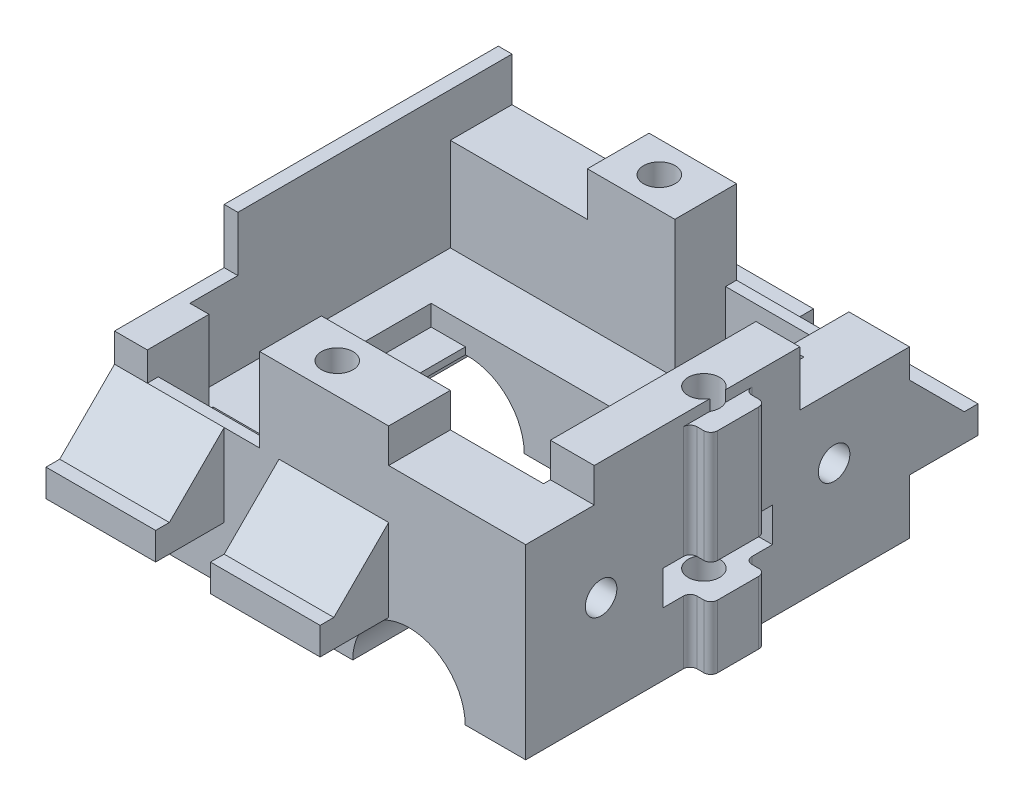
SolidWorks part; units mm, degrees
ref_plane "Front Plane" through (0, 0, 0) normal (0, 0, 1) x (1, 0, 0)
ref_plane "Top Plane" through (0, 0, 0) normal (0, 1, 0) x (1, 0, 0)
ref_plane "Right Plane" through (0, 0, 0) normal (1, 0, 0) x (0, 0, -1)
sketch "Sketch1" plane through (0, 0, 0) normal (1, 0, 0) x (0, 0, -1)
  line L0 (-26.7015, -9.0408) -> (-32.3015, -9.0408) construction
  line L1 (-60.7015, 7.0592) -> (-32.7015, 7.0592)
  line L2 (-60.7015, 7.0592) -> (-60.7015, -9.0408)
  line L3 (-60.7015, -9.0408) -> (-32.7015, -9.0408)
  line L4 (-32.7015, 7.0592) -> (-32.7015, -9.0408)
  dimension "D1" = 16.1
  dimension "D2" = 28
extrude "Boss-Extrude1" add sketch "Sketch1" along normal blind 30
sketch "Sketch2" plane through (0, 0, 60.7015) normal (0, 0, 1) x (1, 0, 0)
  line L7 (30, 7.0592) -> (20, 7.0592)
  line L8 (30, 7.0592) -> (30, 4.5592)
  line L9 (30, 4.5592) -> (20, 4.5592)
  line L10 (20, 7.0592) -> (20, 4.5592)
  dimension "D1" = 10
  dimension "D2" = 2.5
extrude "Cut-Extrude1" cut sketch "Sketch2" against normal blind 5
sketch "Sketch3" plane through (0, 0, 60.7015) normal (0, 0, 1) x (1, 0, 0)
  line L0 (0, 7.0592) -> (0, -9.0408) construction
  line L1 (0, 3.0592) -> (10, 3.0592)
  line L2 (0, 3.0592) -> (0, 7.0592)
  line L3 (0, 7.0592) -> (10, 7.0592)
  line L4 (10, 3.0592) -> (10, 7.0592)
  line L5 (20, 7.0592) -> (0, 7.0592) construction
  dimension "D1" = 4
  dimension "D2" = 10
extrude "Cut-Extrude2" cut sketch "Sketch3" against normal blind 8
sketch "Sketch4" plane through (0, 0, 32.7015) normal (0, 0, -1) x (-1, 0, 0)
  line L6 (-30, 7.0592) -> (0, 7.0592) construction
  line L7 (-1, 7.0592) -> (-11, 7.0592)
  line L8 (-1, 7.0592) -> (-1, 3.8592)
  line L9 (-1, 3.8592) -> (-11, 3.8592)
  line L10 (-11, 7.0592) -> (-11, 3.8592)
  line L11 (0, -9.0408) -> (0, 7.0592) construction
  dimension "D1" = 10
  dimension "D2" = 1
  dimension "D3" = 3.2
extrude "Cut-Extrude3" cut sketch "Sketch4" against normal blind 8
sketch "Sketch5" plane through (0, 0, 32.7015) normal (0, 0, -1) x (-1, 0, 0)
  line L0 (-30, -9.0408) -> (-30, 7.0592) construction
  line L1 (-30, 3.0592) -> (-19, 3.0592)
  line L2 (-30, 3.0592) -> (-30, 7.0592)
  line L3 (-30, 7.0592) -> (-19, 7.0592)
  line L4 (-19, 3.0592) -> (-19, 7.0592)
  line L5 (-30, 7.0592) -> (-11, 7.0592) construction
  dimension "D1" = 4
  dimension "D2" = 11
extrude "Cut-Extrude4" cut sketch "Sketch5" against normal blind 8
sketch "Sketch6" plane through (0, 0, 32.7015) normal (0, 0, -1) x (-1, 0, 0)
  line L0 (-6.4923, -5.0408) -> (-24.9923, -5.0408) construction
  line L1 (-30, -3.0408) -> (-10, -3.0408)
  line L2 (-30, -3.0408) -> (-30, -5.0408)
  line L3 (-30, -5.0408) -> (-10, -5.0408)
  line L4 (-10, -3.0408) -> (-10, -5.0408)
  line L5 (-30, -9.0408) -> (-30, 3.0592) construction
  line L6 (0, -9.0408) -> (0, 7.0592) construction
  dimension "D1" = 0
  dimension "D2" = 10
  dimension "D3" = 2
extrude "Boss-Extrude2" add sketch "Sketch6" along normal blind 5
chamfer "Chamfer1" distance 4 angle 45 1 edges at (20, -3.0408, 32.7015)
sketch "Sketch7" plane through (0, 0, 60.7015) normal (0, 0, 1) x (1, 0, 0)
  line L0 (21.4823, -5.0408) -> (2.9823, -5.0408) construction
  line L1 (0, -3.0408) -> (20, -3.0408)
  line L2 (0, -3.0408) -> (0, -5.0408)
  line L3 (0, -5.0408) -> (20, -5.0408)
  line L4 (20, -3.0408) -> (20, -5.0408)
  line L5 (30, 4.5592) -> (30, -9.0408) construction
  line L6 (0, 3.0592) -> (0, -9.0408) construction
  dimension "D1" = 10
  dimension "D2" = 0
  dimension "D3" = 2
extrude "Boss-Extrude3" add sketch "Sketch7" along normal blind 5
chamfer "Chamfer2" distance 4 angle 45 1 edges at (10, -3.0408, 60.7015)
sketch "Sketch9" plane through (0, 7.0592, 0) normal (0, 1, 0) x (1, 0, 0)
  line L0 (1, -40.7015) -> (1, -32.7015) construction
  line L1 (1, -37.2015) -> (26.8, -37.2015)
  line L2 (1, -37.2015) -> (1, -56.2015)
  line L3 (1, -56.2015) -> (26.8, -56.2015)
  line L4 (26.8, -37.2015) -> (26.8, -56.2015)
  line L5 (30, -32.7015) -> (19, -32.7015) construction
  line L6 (20, -60.7015) -> (10, -60.7015) construction
  line L7 (30, -40.7015) -> (30, -55.7015) construction
  dimension "D1" = 4.5
  dimension "D2" = 4.5
  dimension "D3" = 3.2
extrude "Cut-Extrude6" cut sketch "Sketch9" against normal blind 10
sketch "Sketch13" plane through (0, 0, 60.7015) normal (0, 0, 1) x (1, 0, 0)
  circle A0 centre (21.4823, -9.0408) radius 4.1
  dimension "D1" = 8.2
extrude "Cut-Extrude10" cut sketch "Sketch13" against normal blind 27.2
sketch "Sketch14" plane through (0, 0, 32.7015) normal (0, 0, -1) x (-1, 0, 0)
  circle A0 centre (-6.4923, -9.0408) radius 4.1
  dimension "D1" = 8.2
extrude "Cut-Extrude11" cut sketch "Sketch14" against normal blind 27.2
sketch "Sketch15" plane through (0, -9.0408, 0) normal (0, -1, 0) x (1, 0, 0)
  line L0 (10.5923, 59.9015) -> (10.5923, 32.7015) construction
  line L1 (2.3923, 59.9015) -> (10.5923, 59.9015)
  line L2 (2.3923, 59.9015) -> (2.3923, 55.9015)
  line L3 (2.3923, 55.9015) -> (10.5923, 55.9015)
  line L4 (10.5923, 59.9015) -> (10.5923, 55.9015)
  line L5 (25.5823, 60.7015) -> (25.5823, 33.5015) construction
  line L6 (17.3823, 33.5015) -> (25.5823, 33.5015)
  line L7 (17.3823, 33.5015) -> (17.3823, 37.5015)
  line L8 (17.3823, 37.5015) -> (25.5823, 37.5015)
  line L9 (25.5823, 33.5015) -> (25.5823, 37.5015)
  dimension "D1" = 4
  dimension "D2" = 4
extrude "Cut-Extrude12" cut sketch "Sketch15" against normal blind 27.2
sketch "Sketch16" plane through (0, 7.0592, 0) normal (0, 1, 0) x (1, 0, 0)
  line L1 (10.5923, -59.9015) -> (10, -59.9015)
  line L2 (10.5923, -59.9015) -> (10.5923, -60.7015)
  line L3 (10.5923, -60.7015) -> (10, -60.7015)
  line L4 (10, -59.9015) -> (10, -60.7015)
  line L5 (17.3823, -33.5015) -> (19, -33.5015)
  line L6 (17.3823, -33.5015) -> (17.3823, -32.7015)
  line L7 (17.3823, -32.7015) -> (19, -32.7015)
  line L8 (19, -33.5015) -> (19, -32.7015)
extrude "Cut-Extrude13" cut sketch "Sketch16" against normal up to surface (4 mm away) up to face at (25.3456, 3.0592, 36.0265)
sketch "Sketch17" plane through (0, -9.0408, 0) normal (0, -1, 0) x (1, 0, 0)
  line L0 (30, 60.7015) -> (30, 32.7015) construction
  line L1 (30, 48.7015) -> (31.5, 48.7015)
  line L2 (30, 48.7015) -> (30, 44.7015)
  line L3 (30, 44.7015) -> (31.5, 44.7015)
  line L4 (31.5, 48.7015) -> (31.5, 44.7015)
  line L5 (30, 32.7015) -> (10.5923, 32.7015) construction
  line L6 (30, 60.7015) -> (25.5823, 60.7015) construction
  dimension "D1" = 12
  dimension "D2" = 12
  dimension "D3" = 1.5
extrude "Boss-Extrude4" add sketch "Sketch17" against normal up to surface (16.1 mm away) up to face at (28.4, 7.0592, 48.2015)
fillet "Fillet1" radius 0.5 4 edges at (30, -0.9908, 44.7015) (31.5, -0.9908, 44.7015) (31.5, -0.9908, 48.7015) (30, -0.9908, 48.7015)
sketch "Sketch18" plane through (0, -9.0408, 0) normal (0, -1, 0) x (1, 0, 0)
  line L0 (17.3823, 60.7015) -> (0, 60.7015) construction
  line L1 (0, 60.7015) -> (0, 32.7015) construction
  circle A0 centre (13.985, 46.7015) radius 3.5
  dimension "D1" = 14
  dimension "D2" = 13.985
  dimension "D3" = 7
extrude "Cut-Extrude14" cut sketch "Sketch18" against normal up to surface (6.1 mm away) up to face at (13.9582, -2.9408, 46.7015)
sketch "Sketch19" plane through (31.5, 0, 0) normal (1, 0, 0) x (0, 0, -1)
  line L0 (-32.7015, 0.9592) -> (-32.7015, 3.0592) construction
  line L1 (-50.7015, -1.9408) -> (-42.7015, -1.9408)
  line L2 (-50.7015, -1.9408) -> (-50.7015, -2.9408)
  line L3 (-50.7015, -2.9408) -> (-42.7015, -2.9408)
  line L4 (-42.7015, -1.9408) -> (-42.7015, -2.9408)
  line L5 (-40.7015, 7.0592) -> (-44.2015, 7.0592) construction
  dimension "D1" = 8
  dimension "D2" = 10
  dimension "D3" = 1
  dimension "D4" = 10
extrude "Cut-Extrude15" cut sketch "Sketch19" against normal blind 10
sketch "Sketch20" plane through (0, -2.9408, 0) normal (0, 1, 0) x (1, 0, 0)
  line L0 (10.5923, -56.2015) -> (20, -56.2015) construction
  line L1 (24.3, -41.4015) -> (3.8, -41.4015)
  line L2 (24.3, -41.4015) -> (24.3, -52.0015)
  line L3 (24.3, -52.0015) -> (3.8, -52.0015)
  line L4 (3.8, -41.4015) -> (3.8, -52.0015)
  line L5 (26.8, -55.7015) -> (26.8, -40.7015) construction
  line L6 (17.3823, -37.2015) -> (11, -37.2015) construction
  line L7 (1, -52.7015) -> (1, -32.7015) construction
  dimension "D1" = 4.2
  dimension "D2" = 2.5
  dimension "D3" = 4.2
  dimension "D4" = 2.8
extrude "Cut-Extrude16" cut sketch "Sketch20" against normal blind 1.5
sketch "Sketch21" plane through (0, -2.9408, 0) normal (0, 1, 0) x (1, 0, 0)
  line L0 (24.3, -52.0015) -> (24.3, -41.4015) construction
  line L1 (24.3, -50.7015) -> (30, -50.7015)
  line L2 (24.3, -50.7015) -> (24.3, -42.7015)
  line L3 (24.3, -42.7015) -> (30, -42.7015)
  line L4 (30, -50.7015) -> (30, -42.7015)
extrude "Cut-Extrude17" cut sketch "Sketch21" against normal blind 1.5
sketch "Sketch22" plane through (31.5, 0, 0) normal (1, 0, 0) x (0, 0, -1)
  line L0 (-42.7015, -4.4408) -> (-42.7015, -1.9408) construction
  line L1 (-50.7015, -4.4408) -> (-42.7015, -4.4408)
  line L2 (-50.7015, -4.4408) -> (-50.7015, -1.9408)
  line L3 (-50.7015, -1.9408) -> (-42.7015, -1.9408)
  line L4 (-42.7015, -4.4408) -> (-42.7015, -1.9408)
  dimension "D1" = 2.5
extrude "Cut-Extrude18" cut sketch "Sketch22" against normal blind 1.5
sketch "Sketch23" plane through (0, 7.0592, 0) normal (0, 1, 0) x (1, 0, 0)
  circle A0 centre (29, -46.7015) radius 1.15
  circle A1 centre (14, -34.9515) radius 1.15
  circle A2 centre (14, -58.4515) radius 1.15
  dimension "D1" = 2.3
  dimension "D2" = 2.3
  dimension "D3" = 2.3
extrude "Cut-Extrude19" cut sketch "Sketch23" against normal through all
sketch "Sketch24" plane through (0, 3.0592, 0) normal (0, 1, 0) x (1, 0, 0)
  line L1 (25.5823, -33.5015) -> (17.3823, -33.5015)
  line L2 (25.5823, -33.5015) -> (25.5823, -32.7015)
  line L3 (25.5823, -32.7015) -> (17.3823, -32.7015)
  line L4 (17.3823, -33.5015) -> (17.3823, -32.7015)
  line L5 (2.3923, -59.9015) -> (10.5923, -59.9015)
  line L6 (2.3923, -59.9015) -> (2.3923, -60.7015)
  line L7 (2.3923, -60.7015) -> (10.5923, -60.7015)
  line L8 (10.5923, -59.9015) -> (10.5923, -60.7015)
extrude "Cut-Extrude20" cut sketch "Sketch24" against normal blind 2.1
sketch "Sketch25" plane through (31.5, 0, 0) normal (1, 0, 0) x (0, 0, -1)
  line L0 (-49.2015, 7.0592) -> (-55.7015, 7.0592) construction
  line L1 (-50.5182, 7.0592) -> (-42.5886, 7.0592)
  line L2 (-50.5182, 7.0592) -> (-50.5182, 6.2592)
  line L3 (-50.5182, 6.2592) -> (-42.5886, 6.2592)
  line L4 (-42.5886, 7.0592) -> (-42.5886, 6.2592)
  dimension "D1" = 0.8
extrude "Cut-Extrude21" cut sketch "Sketch25" against normal up to surface (1.5 mm away) up to face at (30, -0.7608, 53.1015)
sketch "Sketch26" plane through (0, 0, 65.7015) normal (0, 0, 1) x (1, 0, 0)
  line L0 (0, -5.0408) -> (20, -5.0408) construction
  line L1 (12, -5.0408) -> (8, -5.0408)
  line L2 (12, -5.0408) -> (12, 0.9592)
  line L3 (12, 0.9592) -> (8, 0.9592)
  line L4 (8, -5.0408) -> (8, 0.9592)
  line L5 (2.3923, 0.9592) -> (10.5923, 0.9592) construction
  line L6 (0, -3.0408) -> (0, 0.9592) construction
  line L7 (20, -5.0408) -> (20, 0.9592) construction
  dimension "D1" = 8
  dimension "D2" = 8
extrude "Cut-Extrude22" cut sketch "Sketch26" against normal up to surface (5 mm away)
sketch "Sketch27" plane through (0, 0, 27.7015) normal (0, 0, -1) x (-1, 0, 0)
  line L0 (-30, -5.0408) -> (-10, -5.0408) construction
  line L1 (-22, -5.0408) -> (-18, -5.0408)
  line L2 (-22, -5.0408) -> (-22, 0.9592)
  line L3 (-22, 0.9592) -> (-18, 0.9592)
  line L4 (-18, -5.0408) -> (-18, 0.9592)
  line L5 (-17.3823, 0.9592) -> (-10, 0.9592) construction
  line L6 (-10, -5.0408) -> (-10, 0.9592) construction
  line L7 (-30, -3.0408) -> (-30, -5.0408) construction
  dimension "D1" = 8
  dimension "D2" = 8
extrude "Cut-Extrude23" cut sketch "Sketch27" against normal up to surface (5 mm away)
sketch "Sketch28" plane through (30, 0, 0) normal (1, 0, 0) x (0, 0, -1)
  line L0 (-60.7015, 4.5592) -> (-60.7015, -9.0408) construction
  line L1 (-32.7015, 0.9592) -> (-32.7015, 3.0592) construction
  line L2 (-60.7015, -9.0408) -> (-49.2015, -9.0408) construction
  line L3 (-44.2015, -9.0408) -> (-32.7015, -9.0408) construction
  circle A0 centre (-55.2015, -1.5408) radius 1.15
  circle A1 centre (-38.2015, -1.5408) radius 1.15
  dimension "D1" = 2.3
  dimension "D2" = 2.3
  dimension "D3" = 5.5
  dimension "D4" = 5.5
  dimension "D5" = 7.5
  dimension "D6" = 7.5
extrude "Cut-Extrude24" cut sketch "Sketch28" against normal up to surface (3.2 mm away) up to face at (26.8, 1.1425, 47.2015)
sketch "Sketch29" plane through (0, -4.4408, 0) normal (0, 1, 0) x (1, 0, 0)
  line L0 (3.8, -52.0015) -> (24.3, -52.0015) construction
  line L1 (21.8, -52.0015) -> (6.3, -52.0015)
  line L2 (21.8, -52.0015) -> (21.8, -41.4015)
  line L3 (21.8, -41.4015) -> (6.3, -41.4015)
  line L4 (6.3, -52.0015) -> (6.3, -41.4015)
  line L5 (24.3, -41.4015) -> (3.8, -41.4015) construction
  line L6 (3.8, -41.4015) -> (3.8, -52.0015) construction
  line L7 (24.3, -52.0015) -> (24.3, -50.7015) construction
  dimension "D1" = 2.5
  dimension "D2" = 2.5
extrude "Cut-Extrude25" cut sketch "Sketch29" against normal up to surface (4.6 mm away) up to face at (14, -9.0408, 59.6015)
